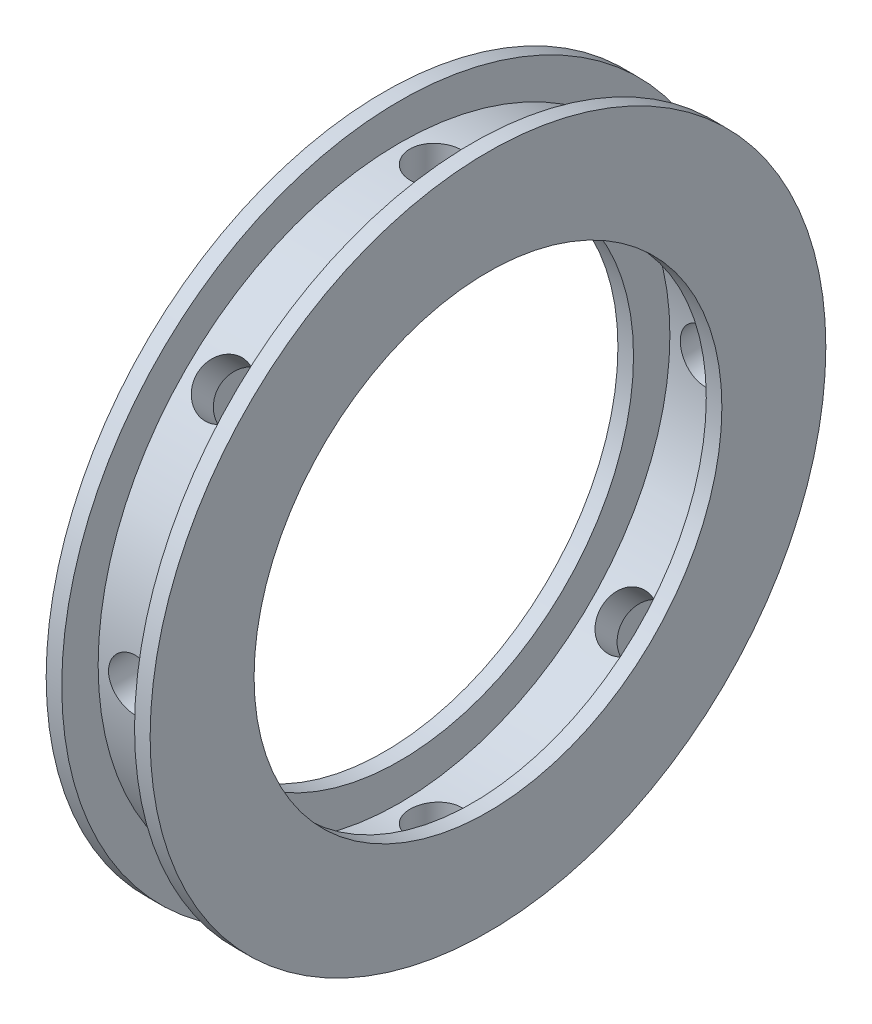
SolidWorks part; units mm, degrees
ref_plane "Front Plane" through (0, 0, 0) normal (0, 0, 1) x (1, 0, 0)
ref_plane "Top Plane" through (0, 0, 0) normal (0, 1, 0) x (1, 0, 0)
ref_plane "Right Plane" through (0, 0, 0) normal (1, 0, 0) x (0, 0, -1)
sketch "Sketch1" plane through (0, 0, 0) normal (0, 0, 1) x (1, 0, 0)
  line L0 (0, 0) -> (10, 0) construction
  line L1 (0, 32.5) -> (0, 22.5)
  line L2 (0, 32.5) -> (1.5, 32.5)
  line L3 (1.5, 32.5) -> (1.5, 29)
  line L4 (1.5, 29) -> (8.5, 29)
  line L5 (8.5, 29) -> (8.5, 32.5)
  line L6 (8.5, 32.5) -> (10, 32.5)
  line L7 (0, 22.5) -> (1.5, 22.5)
  line L8 (1.5, 22.5) -> (1.5, 26)
  line L9 (1.5, 26) -> (8.5, 26)
  line L10 (8.5, 26) -> (8.5, 22.5)
  line L11 (8.5, 22.5) -> (10, 22.5)
  line L12 (10, 22.5) -> (10, 32.5)
  dimension "D1" = 10
  dimension "D2" = 1.5
  dimension "D3" = 45
  dimension "D4" = 52
  dimension "D5" = 58
  dimension "D6" = 65
revolve "Revolve1" add sketch "Sketch1" angle 360 about L0
sketch "Sketch2" plane through (0, 0, 0) normal (0, 1, 0) x (1, 0, 0)
  line L0 (5, 29) -> (5, 0) construction
  line L1 (8.5, 29) -> (1.5, 29) construction
  circle A0 centre (5, 0) radius 2.5
  point P3 (0, 0)
  point P7 (0, 0)
  dimension "D1" = 5
extrude "Cut-Extrude1" cut sketch "Sketch2" against normal through all
pattern_circular "CirPattern1" count 8 over 360 about axis through (0, 0, 0) along (-1, 0, 0) of "Cut-Extrude1"
